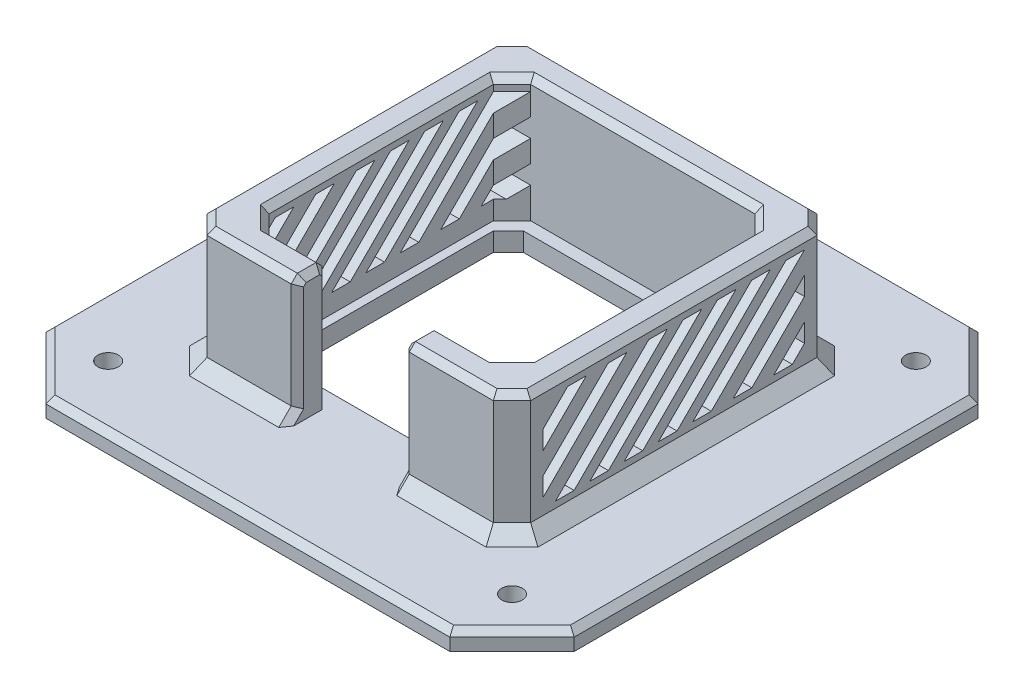
SolidWorks part; units mm, degrees
ref_plane "前视基准面" through (0, 0, 0) normal (0, 0, 1) x (1, 0, 0)
ref_plane "上视基准面" through (0, 0, 0) normal (0, 1, 0) x (1, 0, 0)
ref_plane "右视基准面" through (0, 0, 0) normal (1, 0, 0) x (0, 0, -1)
other "Configuration Table"
sketch "草图1" plane through (0, 0, 0) normal (0, 1, 0) x (1, 0, 0)
  line L1 (0, 0) -> (85, 0)
  line L2 (0, 0) -> (0, 85)
  line L3 (0, 85) -> (85, 85)
  line L4 (85, 0) -> (85, 85)
  dimension "D1" = 85
  dimension "D2" = 85
extrude "凸台-拉伸1" add sketch "草图1" along normal blind 3
sketch "草图2" plane through (0, 3, 0) normal (0, 1, 0) x (1, 0, 0)
  line L0 (0, 85) -> (85, 0) construction
  line L1 (85, 85) -> (0, 0) construction
  line L2 (0, 0) -> (0, 85) construction
  line L3 (85, 85) -> (85, 0) construction
  line L4 (85, 0) -> (0, 0) construction
  line L5 (0, 85) -> (85, 85) construction
  line L6 (16.46, 68.54) -> (68.54, 68.54)
  line L7 (21.46, 21.46) -> (63.54, 21.46)
  line L8 (21.46, 21.46) -> (21.46, 63.54)
  line L9 (21.46, 63.54) -> (63.54, 63.54)
  line L10 (63.54, 21.46) -> (63.54, 63.54)
  line L11 (21.46, 21.46) -> (63.54, 63.54) construction
  line L12 (21.46, 63.54) -> (63.54, 21.46) construction
  line L13 (68.54, 16.46) -> (68.54, 68.54)
  line L14 (16.46, 16.46) -> (68.54, 16.46)
  line L15 (16.46, 16.46) -> (16.46, 68.54)
  point P8 (42.5, 42.5)
  dimension "D1" = 42.08
  dimension "D2" = 42.08
  dimension "D3" = 5
extrude "凸台-拉伸2" add sketch "草图2" along normal blind 20
chamfer "倒角1" distance 3 angle 45 8 edges at (68.54, 13, -16.46) (68.54, 13, -68.54) (16.46, 13, -16.46) (16.46, 13, -68.54) (63.54, 13, -21.46) (21.46, 13, -21.46) (63.54, 13, -63.54) (21.46, 13, -63.54)
chamfer "倒角2" distance 2 angle 45 8 edges at (16.46, 3, -42.5) (17.96, 3, -67.04) (42.5, 3, -68.54) (67.04, 3, -67.04) (68.54, 3, -42.5) (67.04, 3, -17.96) (17.96, 3, -17.96) (42.5, 3, -16.46)
chamfer "倒角3" distance 1 angle 45 16 edges at (62.04, 23, -62.04) (42.5, 23, -63.54) (22.96, 23, -62.04) (21.46, 23, -42.5) (22.96, 23, -22.96) (42.5, 23, -21.46) (62.04, 23, -22.96) (63.54, 23, -42.5) (17.96, 23, -17.96) (16.46, 23, -42.5) (17.96, 23, -67.04) (42.5, 23, -68.54) (67.04, 23, -67.04) (68.54, 23, -42.5) (67.04, 23, -17.96) (42.5, 23, -16.46)
chamfer "倒角4" distance 10 angle 45 4 edges at (0, 1.5, -85) (0, 1.5, 0) (85, 1.5, -85) (85, 1.5, 0)
chamfer "倒角5" distance 1 angle 45 8 edges at (0, 3, -42.5) (5, 3, -5) (42.5, 3, 0) (80, 3, -5) (42.5, 3, -85) (85, 3, -42.5) (80, 3, -80) (5, 3, -80)
sketch "草图3" plane through (0, 23, 0) normal (0, 1, 0) x (1, 0, 0)
  line L0 (42.5, 30.2716) -> (42.5, 7.8936)
  line L1 (34, 30.2716) -> (51, 30.2716)
  line L2 (34, 30.2716) -> (34, 7.8936)
  line L3 (34, 7.8936) -> (51, 7.8936)
  line L4 (51, 30.2716) -> (51, 7.8936)
  line L5 (42.5, 84) -> (42.5, 1)
  line L6 (74.5858, 84) -> (10.4142, 84) construction
  line L7 (10.4142, 1) -> (74.5858, 1) construction
  line M8 (60.9542, 20.46) -> (24.0458, 20.46)
  line M14 (19.8742, 17.46) -> (65.1258, 17.46)
  dimension "D1" = 8.5
extrude "切除-拉伸1" cut sketch "草图3" against normal up to surface (20 mm away) contours L4 L0 L3 M14 | L4 L0 M8 M14 | L4 L1 L0 M8 | L1 L2 L0 M8 | L2 L0 M8 M14 | L2 L3 L0 M14 up to face at (42.5, 3, -42.5)
chamfer "倒角6" distance 1 angle 45 12 edges at (51, 12.5, -21.46) (51, 22.5, -20.96) (51, 23, -18.96) (51, 22.5, -16.96) (51, 13.5, -16.46) (51, 4, -15.46) (34, 4, -15.46) (34, 13.5, -16.46) (34, 22.5, -16.96) (34, 23, -18.96) (34, 22.5, -20.96) (34, 12.5, -21.46)
sketch "草图4" plane through (0, 3, 0) normal (0, 1, 0) x (1, 0, 0)
  line L0 (63.54, 60.54) -> (60.54, 63.54) construction
  line L1 (52, 21.46) -> (60.54, 21.46) construction
  line L2 (60.54, 21.46) -> (63.54, 24.46) construction
  line L3 (63.54, 24.46) -> (63.54, 60.54) construction
  line L4 (24.46, 21.46) -> (33, 21.46) construction
  line L5 (21.46, 24.46) -> (24.46, 21.46) construction
  line L6 (24.46, 63.54) -> (21.46, 60.54) construction
  line L7 (60.54, 63.54) -> (24.46, 63.54) construction
  line L8 (63.54, 60.54) -> (60.54, 63.54)
  line L9 (52, 21.46) -> (60.54, 21.46)
  line L10 (60.54, 21.46) -> (63.54, 24.46)
  line L11 (63.54, 24.46) -> (63.54, 60.54)
  line L12 (24.46, 21.46) -> (33, 21.46)
  line L13 (21.46, 24.46) -> (24.46, 21.46)
  line L14 (24.46, 63.54) -> (21.46, 60.54)
  line L15 (60.54, 63.54) -> (24.46, 63.54)
  line L16 (33, 21.46) -> (52, 21.46)
  line L17 (22.8742, 25.8742) -> (25.2884, 23.46)
  line L18 (25.2884, 23.46) -> (33, 23.46)
  line L19 (33, 23.46) -> (52, 23.46)
  line L20 (52, 23.46) -> (59.7116, 23.46)
  line L21 (59.7116, 23.46) -> (61.54, 25.2884)
  line L22 (61.54, 25.2884) -> (61.54, 59.7116)
  line L23 (61.54, 59.7116) -> (59.7116, 61.54)
  line L24 (59.7116, 61.54) -> (25.2884, 61.54)
  line L25 (25.2884, 61.54) -> (22.8742, 59.1258)
  line L26 (22.8742, 59.1258) -> (22.8742, 25.8742)
  dimension "D1" = 2
extrude "切除-拉伸2" cut sketch "草图4" against normal blind 10 contours L25 L26 L17 L18 L19 L20 L21 L22 L23 L24
sketch "草图5" plane through (16.46, 0, 0) normal (-1, 0, 0) x (0, 0, 1)
  line L0 (-63.54, 21) -> (-48.54, 6)
  line L1 (-48.54, 6) -> (-45.54, 6)
  line L2 (-45.54, 6) -> (-60.54, 21)
  line L3 (-60.54, 21) -> (-63.54, 21)
  line L4 (-19.46, 22) -> (-65.54, 22) construction
  line L5 (-65.54, 5) -> (-19.46, 5) construction
  line L6 (-58.02, 21) -> (-43.02, 6)
  line L7 (-43.02, 6) -> (-40.02, 6)
  line L8 (-40.02, 6) -> (-55.02, 21)
  line L9 (-55.02, 21) -> (-58.02, 21)
  line L10 (-52.5, 21) -> (-37.5, 6)
  line L11 (-37.5, 6) -> (-34.5, 6)
  line L12 (-34.5, 6) -> (-49.5, 21)
  line L13 (-49.5, 21) -> (-52.5, 21)
  line L14 (-46.98, 21) -> (-31.98, 6)
  line L15 (-31.98, 6) -> (-28.98, 6)
  line L16 (-28.98, 6) -> (-43.98, 21)
  line L17 (-43.98, 21) -> (-46.98, 21)
  line L18 (-41.46, 21) -> (-26.46, 6)
  line L19 (-26.46, 6) -> (-23.46, 6)
  line L20 (-23.46, 6) -> (-38.46, 21)
  line L21 (-38.46, 21) -> (-41.46, 21)
  line L24 (-45.54, 6) -> (-43.02, 6)
  line L25 (-40.02, 6) -> (-37.5, 6)
  line L26 (-34.5, 6) -> (-31.98, 6)
  line L27 (-28.98, 6) -> (-26.46, 6)
  line L28 (-48.54, 6) -> (-52.06, 6)
  line L29 (-52.06, 6) -> (-55.06, 6)
  line L30 (-55.06, 6) -> (-58.58, 6)
  line L31 (-58.58, 6) -> (-61.58, 6)
  line L32 (-61.58, 6) -> (-63.54, 6)
  line L33 (-52.06, 6) -> (-63.54, 17.48)
  line L34 (-63.54, 17.48) -> (-63.54, 14.48)
  line L35 (-63.54, 14.48) -> (-55.06, 6)
  line L36 (-58.58, 6) -> (-63.54, 10.96)
  line L37 (-63.54, 10.96) -> (-63.54, 7.96)
  line L38 (-63.54, 7.96) -> (-61.58, 6)
  line L39 (-38.46, 21) -> (-34.94, 21)
  line L40 (-34.94, 21) -> (-31.94, 21)
  line L41 (-31.94, 21) -> (-28.42, 21)
  line L42 (-28.42, 21) -> (-25.42, 21)
  line L43 (-34.94, 21) -> (-21.46, 7.52)
  line L44 (-21.46, 7.52) -> (-21.46, 10.52)
  line L45 (-21.46, 10.52) -> (-31.94, 21)
  line L46 (-28.42, 21) -> (-21.46, 14.04)
  line L47 (-21.46, 14.04) -> (-21.46, 17.04)
  line L48 (-21.46, 17.04) -> (-25.42, 21)
  line L50 (-16.46, 22) -> (-16.46, 5) construction
  line L52 (-68.54, 5) -> (-68.54, 22) construction
  line L53 (-25.42, 21) -> (-21.9, 21)
  line L54 (-21.9, 21) -> (-21.46, 21)
  line L55 (-21.46, 21) -> (-21.46, 20.56)
  line L56 (-21.46, 20.56) -> (-21.46, 17.04)
  line L57 (-21.46, 20.56) -> (-21.9, 21)
  dimension "D1" = 45
  dimension "D2" = 45
  dimension "D3" = 1
  dimension "D4" = 1
  dimension "D5" = 3
  dimension "D6" = 5
  dimension "D7" = 5
  dimension "D8" = 2.52
  dimension "D9" = 3
  dimension "D10" = 3.52
  dimension "D11" = 3
  dimension "D12" = 3.52
  dimension "D13" = 3
  dimension "D14" = 3.52
  dimension "D15" = 3.52
  dimension "D16" = 3
  dimension "D17" = 3
  dimension "D18" = 3.52
extrude "切除-拉伸4" cut sketch "草图5" against normal blind 59 contours L37 L38 L31 L36 | L34 L35 L29 L33 | L2 L3 L0 L1 | L8 L9 L6 L7 | L12 L13 L10 L11 | L16 L17 L14 L15 | L20 L21 L18 L19 | L44 L45 L40 L43 | L47 L48 L42 L46
sketch "草图6" plane through (0, 0, 0) normal (0, -1, 0) x (1, 0, 0)
  line L0 (10, -10) -> (75, -10) construction
  line L1 (10, -10) -> (10, -75) construction
  line L2 (10, -75) -> (75, -75) construction
  line L3 (75, -75) -> (75, -10) construction
  line L8 (0, -10) -> (0, -75)
  line L9 (0, -75) -> (10, -85)
  line L10 (10, -85) -> (75, -85)
  line L11 (75, -85) -> (85, -75)
  line L12 (85, -75) -> (85, -10)
  line L13 (85, -10) -> (75, 0)
  line L14 (75, 0) -> (10, 0)
  line L15 (10, 0) -> (0, -10)
  line L16 (0, -10) -> (0, -75)
  line L17 (0, -75) -> (10, -85)
  line L18 (10, -85) -> (75, -85)
  line L19 (75, -85) -> (85, -75)
  line L20 (85, -75) -> (85, -10)
  line L21 (85, -10) -> (75, 0)
  line L22 (75, 0) -> (10, 0)
  line L23 (10, 0) -> (0, -10)
  circle A0 centre (10, -10) radius 1.65
  circle A1 centre (75, -10) radius 1.65
  circle A2 centre (75, -75) radius 1.65
  circle A3 centre (10, -75) radius 1.65
  dimension "D2" = 3.3
  dimension "D3" = 10
  dimension "D4" = 10
  dimension "D5" = 10
  dimension "D6" = 10
  dimension "D7" = 10
  dimension "D8" = 10
  dimension "D1" = 0
extrude "切除-拉伸5" cut sketch "草图6" against normal blind 10 contours A1 | A2 | A3 | A0
